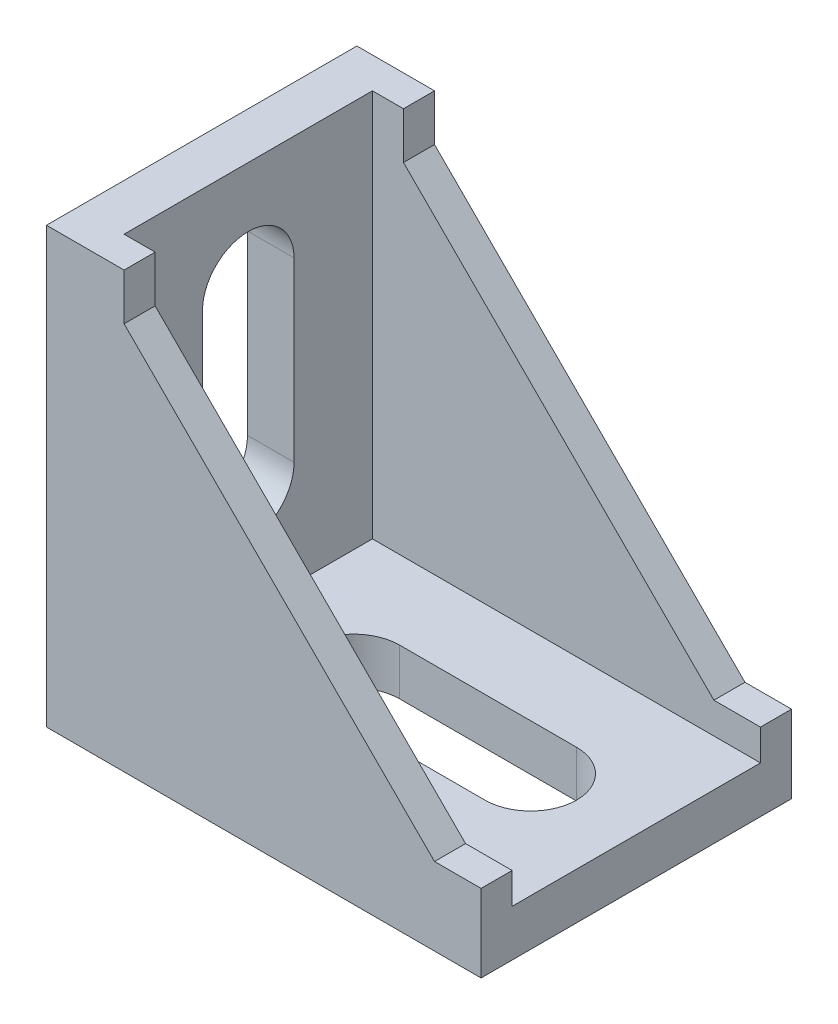
SolidWorks part; units mm, degrees
ref_plane "Front Plane" through (0, 0, 0) normal (0, 0, 1) x (1, 0, 0)
ref_plane "Top Plane" through (0, 0, 0) normal (0, 1, 0) x (1, 0, 0)
ref_plane "Right Plane" through (0, 0, 0) normal (1, 0, 0) x (0, 0, -1)
sketch "Sketch2" plane through (0, 0, 0) normal (0, 0, 1) x (1, 0, 0)
  line L0 (0, 0) -> (0, 28)
  line L1 (0, 28) -> (3, 28)
  line L2 (3, 28) -> (3, 3)
  line L3 (3, 3) -> (28, 3)
  line L4 (28, 3) -> (28, 0)
  line L5 (28, 0) -> (0, 0)
  dimension "D1" = 28
  dimension "D2" = 3
extrude "Boss-Extrude1" add sketch "Sketch2" against normal blind 20
sketch "Sketch4" plane through (0, 3, 0) normal (0, 1, 0) x (1, 0, 0)
  line L0 (0, 10) -> (28, 10) construction
  line L1 (0, 20) -> (0, 0) construction
  line L2 (28, 20) -> (28, 0) construction
  line L3 (15.5, 20) -> (15.5, 0) construction
  line L4 (28, 20) -> (3, 20) construction
  line L5 (28, 0) -> (3, 0) construction
  line L6 (9.8, 10) -> (21.2, 10) construction
  line L7 (9.8, 12.95) -> (21.2, 12.95)
  line L8 (9.8, 7.05) -> (21.2, 7.05)
  arc A0 (9.8, 12.95) -> (9.8, 7.05) centre (9.8, 10) ccw
  arc A1 (21.2, 7.05) -> (21.2, 12.95) centre (21.2, 10) ccw
  point P14 (15.5, 10)
  dimension "D1" = 11.4
  dimension "D2" = 5.9
extrude "Cut-Extrude1" cut sketch "Sketch4" against normal blind 10
sketch "Sketch5" plane through (3, 0, 0) normal (1, 0, 0) x (0, 0, -1)
  line L0 (10, 28) -> (10, 0) construction
  line L1 (20, 28) -> (0, 28) construction
  line L2 (20, 0) -> (0, 0) construction
  line L3 (0, 15.5) -> (20, 15.5) construction
  line L4 (0, 3) -> (0, 28) construction
  line L5 (20, 3) -> (20, 28) construction
  line L6 (10, 21.2) -> (10, 9.8) construction
  line L7 (12.95, 21.2) -> (12.95, 9.8)
  line L8 (7.05, 21.2) -> (7.05, 9.8)
  arc A0 (12.95, 21.2) -> (7.05, 21.2) centre (10, 21.2) ccw
  arc A1 (7.05, 9.8) -> (12.95, 9.8) centre (10, 9.8) ccw
  point P14 (10, 15.5)
  dimension "D1" = 5.9
  dimension "D2" = 11.4
extrude "Cut-Extrude2" cut sketch "Sketch5" against normal blind 10
sketch "Sketch6" plane through (0, 0, 0) normal (0, 0, 1) x (1, 0, 0)
  line L0 (3, 28) -> (5, 28)
  line L1 (5, 28) -> (5, 25)
  line L2 (5, 25) -> (25, 5)
  line L3 (25, 5) -> (28, 5)
  line L4 (28, 5) -> (28, 3)
  line L5 (3, 3) -> (3, 28) construction
  line L6 (28, 3) -> (3, 3) construction
  line L7 (3, 28) -> (3, 3)
  line L8 (3, 3) -> (28, 3)
  dimension "D1" = 2
  dimension "D2" = 2
  dimension "D3" = 135
  dimension "D4" = 20
extrude "Boss-Extrude2" add sketch "Sketch6" against normal blind 2
ref_plane "Plane1" through (0, 0, -10) normal (0, 0, -1) x (-1, 0, 0)
mirror "Mirror4" about plane through (0, 0, -10) normal (0, 0, -1) of "Boss-Extrude2"
